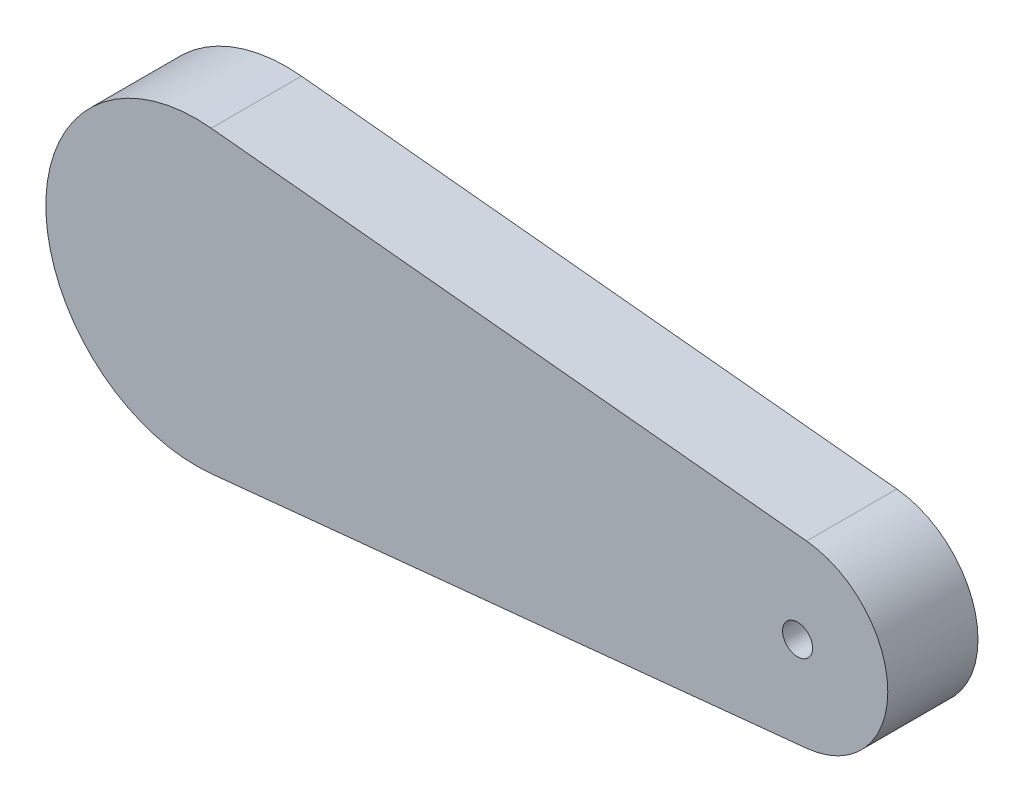
SolidWorks part; units mm, degrees
ref_plane "Front Plane" through (0, 0, 0) normal (0, 0, 1) x (1, 0, 0)
ref_plane "Top Plane" through (0, 0, 0) normal (0, 1, 0) x (1, 0, 0)
ref_plane "Right Plane" through (0, 0, 0) normal (1, 0, 0) x (0, 0, -1)
sketch "Sketch1" plane through (0, 0, 0) normal (0, 0, 1) x (1, 0, 0)
  line L0 (5, 49.7494) -> (203, 29.8496)
  line L1 (5, -49.7494) -> (203, -29.8496)
  arc A0 (5, 49.7494) -> (5, -49.7494) centre (0, 0) ccw
  arc A1 (203, -29.8496) -> (203, 29.8496) centre (200, 0) ccw
  dimension "D1" = 100
  dimension "D2" = 60
  dimension "D3" = 200
extrude "Boss-Extrude1" add sketch "Sketch1" along normal blind 30
sketch "Sketch2" plane through (0, 0, 0) normal (0, 0, -1) x (-1, 0, 0)
  circle A0 centre (0, 0) radius 5
  dimension "D1" = 10
extrude "Cut-Extrude1" cut sketch "Sketch2" against normal blind 10
sketch "Sketch3" plane through (0, 0, 30) normal (0, 0, 1) x (1, 0, 0)
  circle A0 centre (200, 0) radius 5
  arc A1 (203, -29.8496) -> (203, 29.8496) centre (200, 0) ccw construction
  dimension "D1" = 10
extrude "Cut-Extrude2" cut sketch "Sketch3" against normal blind 10
ref_plane "Plane1" through (0, 0, -222) normal (0, 0, 1) x (1, 0, 0)
sketch "Sketch4" plane through (0, 0, 30) normal (0, 0, 1) x (1, 0, 0)
  line L0 (0, 0) -> (200, 0) construction
